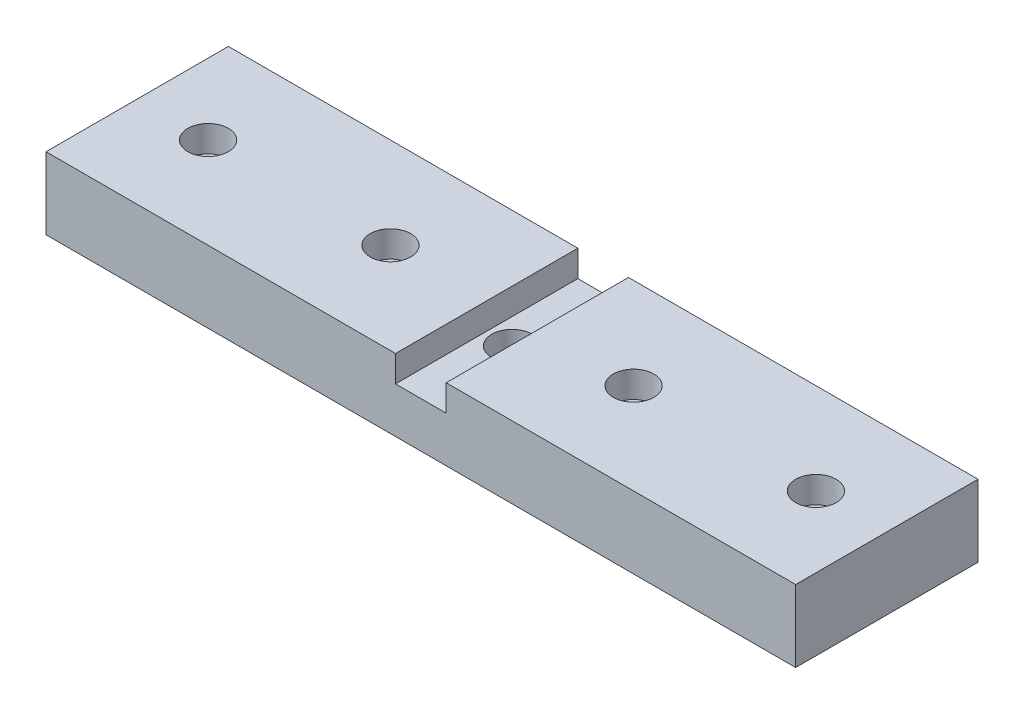
SolidWorks part; units mm, degrees
ref_plane "前视基准面" through (0, 0, 0) normal (0, 0, 1) x (1, 0, 0)
ref_plane "上视基准面" through (0, 0, 0) normal (0, 1, 0) x (1, 0, 0)
ref_plane "右视基准面" through (0, 0, 0) normal (1, 0, 0) x (0, 0, -1)
sketch "草图1" plane through (0, 0, 0) normal (0, 1, 0) x (1, 0, 0)
  line L1 (185, -45) -> (-185, -45)
  line L2 (185, -45) -> (185, 45)
  line L3 (185, 45) -> (-185, 45)
  line L4 (-185, -45) -> (-185, 45)
  line L5 (185, -45) -> (-185, 45) construction
  line L6 (185, 45) -> (-185, -45) construction
  point P0 (0, 0)
  dimension "D1" = 370
  dimension "D2" = 90
extrude "凸台-拉伸1" add sketch "草图1" along normal blind 35.5
sketch "草图2" plane through (0, 35.5, 0) normal (0, 1, 0) x (1, 0, 0)
  line L0 (0, 45) -> (0, -45) construction
  line L1 (185, 45) -> (-185, 45) construction
  line L2 (-185, -45) -> (185, -45) construction
  line L3 (-12.5, 45) -> (-12.5, -45)
  line L4 (12.5, -45) -> (12.5, 45)
  line L5 (-12.5, 45) -> (12.5, 45)
  line L6 (12.5, -45) -> (-12.5, -45)
  dimension "D1" = 25
extrude "切除-拉伸1" cut sketch "草图2" against normal blind 13
hole_wizard "M4 六角头螺栓的柱形沉头孔1" positions "草图5" profile "草图4" counterbore size "M4" standard "GB" end condition through all
sketch "草图5" plane through (0, 35.5, 0) normal (0, 1, 0) x (1, 0, 0)
  line L0 (-12.5, 45) -> (-185, 45) construction
  line L1 (-185, 45) -> (-185, -45) construction
  point P0 (-150, 0)
  dimension "D1" = 45
  dimension "D2" = 35
sketch "草图4" plane through (-150, 35.5, 0) normal (1, 0, 0) x (0, 0, 1)
  line L0 (0, 0) -> (0, 35.5)
  line L1 (0, 35.5) -> (6.75, 35.5)
  line L3 (6.75, 35.5) -> (6.75, 13)
  line L4 (6.75, 13) -> (10, 13)
  line L5 (10, 13) -> (10, 0)
  line L7 (10, 0) -> (0, 0)
  line L11 (0, -6.35) -> (0, 107.95) construction
  dimension "通孔孔直径" = 13.5
  dimension "通孔孔深度" = 35.5
  dimension "柱形沉头孔直径" = 20
  dimension "柱形沉头孔深度" = 13
pattern_linear "阵列(线性)1" count 2 spacing 90 along (1, 0, 0) of "M4 六角头螺栓的柱形沉头孔1"
pattern_linear "阵列(线性)2" count 2 spacing 120 along (1, 0, 0) of "阵列(线性)1"
pattern_linear "阵列(线性)3" count 2 spacing 90 along (1, 0, 0) of "阵列(线性)2"
hole_wizard "M4 六角头螺栓的柱形沉头孔2" positions "草图6" profile "草图7" counterbore size "M4" standard "GB" end condition through all
sketch "草图6" plane through (0, 22.5, 0) normal (0, 1, 0) x (1, 0, 0)
  point P0 (0, 0)
sketch "草图7" plane through (0, 22.5, 0) normal (1, 0, 0) x (0, 0, 1)
  line L0 (0, 0) -> (0, 22.5)
  line L1 (0, 22.5) -> (6.75, 22.5)
  line L3 (6.75, 22.5) -> (6.75, 13)
  line L4 (6.75, 13) -> (10, 13)
  line L5 (10, 13) -> (10, 0)
  line L7 (10, 0) -> (0, 0)
  line L11 (0, -6.35) -> (0, 107.95) construction
  dimension "通孔孔直径" = 13.5
  dimension "通孔孔深度" = 22.5
  dimension "柱形沉头孔直径" = 20
  dimension "柱形沉头孔深度" = 13
